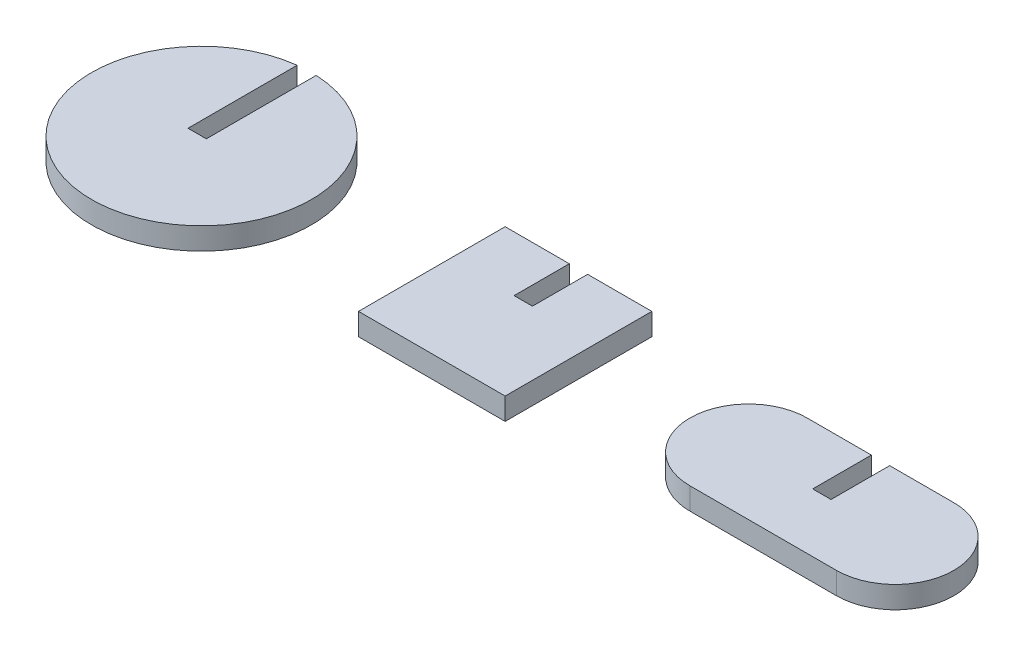
SolidWorks part; units mm, degrees
ref_plane "Front Plane" through (0, 0, 0) normal (0, 0, 1) x (1, 0, 0)
ref_plane "Top Plane" through (0, 0, 0) normal (0, 1, 0) x (1, 0, 0)
ref_plane "Right Plane" through (0, 0, 0) normal (1, 0, 0) x (0, 0, -1)
sketch "Sketch1" plane through (0, 0, 0) normal (0, 1, 0) x (1, 0, 0)
  line L5 (104.8763, -1.8089) -> (124.8763, -1.8089) construction
  line L11 (2.0464, -1.8089) -> (202.0464, -1.8089) construction
  line L15 (28.4354, 13.078) -> (28.4354, -1.8089)
  line L16 (28.4354, -1.8089) -> (30.9354, -1.8089)
  line L17 (30.9354, 13.1765) -> (30.9354, -1.8089)
  line L25 (61.6873, -11.8089) -> (81.6873, -11.8089)
  line L26 (61.6873, -11.8089) -> (61.6873, 8.1911)
  line L27 (61.6873, 8.1911) -> (70.4373, 8.1911)
  line L28 (81.6873, -11.8089) -> (81.6873, 8.1911)
  line L29 (61.6873, -11.8089) -> (71.6873, -1.8089) construction
  line L30 (61.6873, 8.1911) -> (70.4373, -0.5589) construction
  line L42 (72.9373, 8.1911) -> (81.6873, 8.1911)
  line L43 (71.6873, -1.8089) -> (81.6873, -11.8089) construction
  line L44 (72.9373, -0.5589) -> (81.6873, 8.1911) construction
  line L47 (104.8763, 6.1911) -> (113.6263, 6.1911)
  line L48 (70.4373, 0.6584) -> (72.9373, 0.6584)
  line L49 (70.4373, 0.6584) -> (70.4373, 8.1911)
  line L51 (72.9373, 0.6584) -> (72.9373, 8.1911)
  line L52 (104.8763, -9.8089) -> (124.8763, -9.8089)
  line L53 (116.1263, 6.1911) -> (124.8763, 6.1911)
  line L54 (113.6263, -1.8089) -> (116.1263, -1.8089)
  line L55 (113.6263, -1.8089) -> (113.6263, 6.1911)
  line L57 (116.1263, -1.8089) -> (116.1263, 6.1911)
  arc A0 (28.4354, 13.078) -> (30.9354, 13.1765) centre (30.2741, -1.8089) ccw
  arc A1 (104.8763, 6.1911) -> (104.8763, -9.8089) centre (104.8763, -1.8089) ccw
  arc A2 (124.8763, -9.8089) -> (124.8763, 6.1911) centre (124.8763, -1.8089) ccw
  point P7 (71.6873, -1.8089)
  point P16 (30.2741, 13.1911)
  point P28 (71.6873, 5.6584)
  point P36 (154.3539, 0.6584)
  dimension "D3" = 30
  dimension "D11" = 8
  dimension "D4" = 2.5
  dimension "D5" = 2.5
  dimension "D6" = 20
  dimension "D7" = 20
  dimension "D9" = 200
  dimension "D10" = 20
  dimension "D12" = 2.5
extrude "Boss-Extrude1" add sketch "Sketch1" along normal blind 3
equation "\"k\" = 0.52mm'kerf"
equation "\"t\" = 2.72mm'thickness"
equation "\"w\" = 20mm'piece width"
equation "\"c\"= 0.3mm'clearance"
equation "\"s\"= \"t\" - \"k\" + \"c\"'slot opening"
